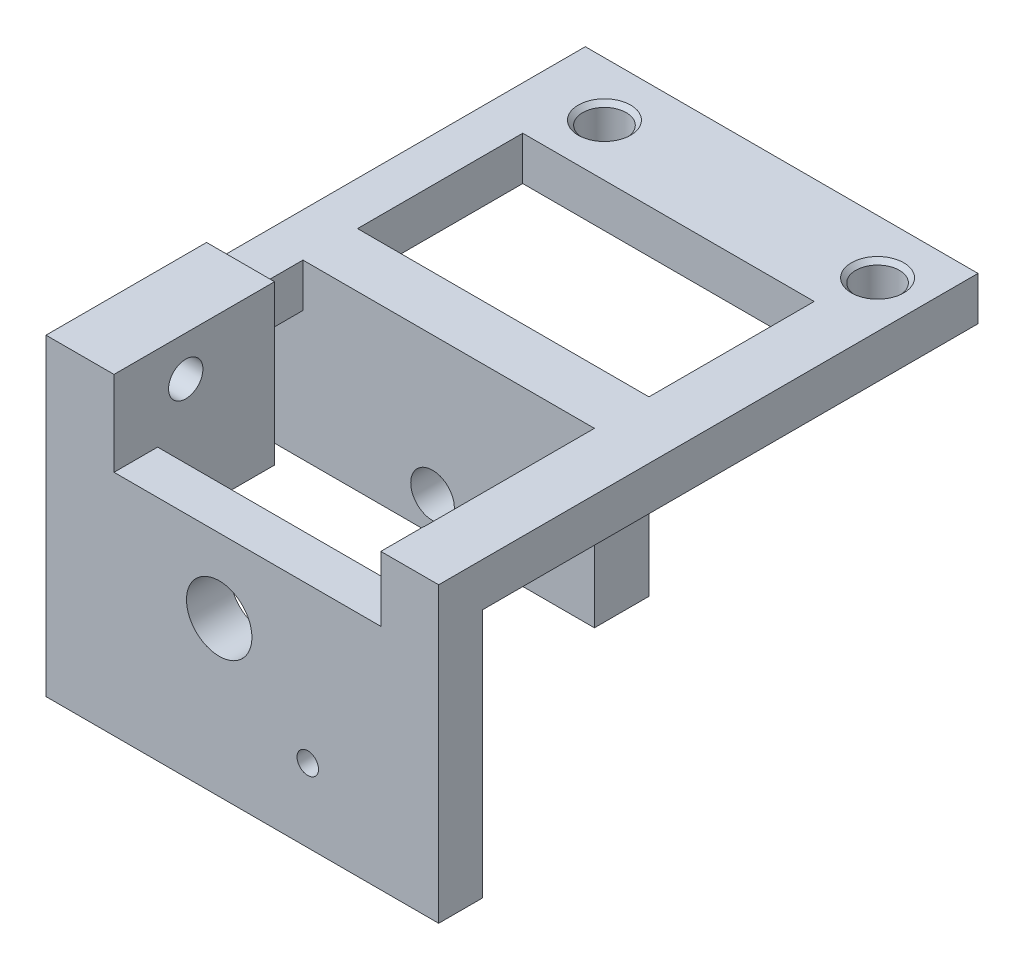
SolidWorks part; units mm, degrees
material "ABS"
ref_plane "Front Plane" through (0, 0, 0) normal (0, 0, 1) x (1, 0, 0)
ref_plane "Top Plane" through (0, 0, 0) normal (0, 1, 0) x (1, 0, 0)
ref_plane "Right Plane" through (0, 0, 0) normal (1, 0, 0) x (0, 0, -1)
sketch "Sketch1" plane through (0, 0, 0) normal (0, 0, 1) x (1, 0, 0)
  line L0 (0, 8.8442) -> (12.8921, -2.9343) construction
  line L1 (23.5226, 29.0697) -> (31.9421, 29.0697)
  line L2 (-25.2079, 8.8442) -> (-25.2079, -13.6023)
  line L3 (-25.2079, -13.6023) -> (31.9421, -13.6023)
  line L4 (31.9421, 29.0697) -> (31.9421, -13.6023)
  line L6 (-25.2079, 8.8442) -> (-25.2079, 31.9582)
  line L7 (-25.2079, 31.9582) -> (-18.8579, 31.9582)
  line L11 (23.5226, 22.6565) -> (23.5226, 29.0697)
  line L12 (-18.8579, 31.9582) -> (-15.3109, 31.9582)
  line L14 (-15.3109, 31.9582) -> (-15.3109, 22.6565)
  line L15 (-15.3109, 22.6565) -> (-15.3109, 19.6203)
  line L16 (-15.3109, 19.6203) -> (23.5226, 19.6203)
  line L17 (23.5226, 19.6203) -> (23.5226, 22.6565)
  circle A0 centre (12.8921, -2.9343) radius 1.5615
  circle A1 centre (0, 8.8442) radius 4.7625
  point P6 (0, 0)
  dimension "D5" = 9.525
  dimension "D1" = 23.114
  dimension "D2" = 57.15
  dimension "D3" = 42.672
  dimension "D4" = 6.35
  dimension "D6" = 19.05
  dimension "D7" = 10.668
  dimension "D8" = 17.4625
extrude "Boss-Extrude1" add sketch "Sketch1" against normal blind 6.35
sketch "Sketch2" plane through (0, 0, 0) normal (0, 0, 1) x (1, 0, 0)
  line L0 (-25.2079, 31.9582) -> (-25.2079, -13.6023) construction
  line L1 (-18.8579, 31.9582) -> (-25.2079, 31.9582)
  line L3 (-18.8579, 8.8442) -> (-25.2079, 8.8442)
  line L4 (-25.2079, 31.9582) -> (-25.2079, 8.8442)
  line L6 (-15.3109, 31.9582) -> (-25.2079, 31.9582)
  line L7 (-15.3109, 31.9582) -> (-15.3109, 8.8442)
  line L8 (-15.3109, 8.8442) -> (-25.2079, 8.8442)
  line L9 (-25.2079, 31.9582) -> (-25.2079, 8.8442)
  line M4 (-15.3109, 31.9582) -> (-25.2079, 31.9582)
  line M5 (-25.2079, 31.9582) -> (-25.2079, -13.6023)
  line M15 (-15.3109, 19.6203) -> (-15.3109, 31.9582)
  dimension "D1" = 23.114
extrude "Boss-Extrude2" add sketch "Sketch2" against normal blind 23.368 contours L8 L7 L3 M15 M4 M5
sketch "Sketch3" plane through (0, 29.0697, 0) normal (0, 1, 0) x (1, 0, 0)
  line L0 (-25.2079, 23.368) -> (-25.2079, 0) construction
  line L1 (-18.8579, 0) -> (-25.2079, 0)
  line L2 (-18.8579, 0) -> (-18.8579, 76.2)
  line L3 (-18.8579, 76.2) -> (-25.2079, 76.2)
  line L4 (-25.2079, 0) -> (-25.2079, 76.2)
  line L5 (31.9421, 0) -> (23.5601, 0)
  line L6 (31.9421, 0) -> (31.9421, 76.2)
  line L7 (31.9421, 76.2) -> (23.5601, 76.2)
  line L8 (23.5601, 0) -> (23.5601, 76.2)
  dimension "D2" = 8.382
  dimension "D3" = 76.2
  dimension "D4" = 76.2
extrude "Boss-Extrude3" add sketch "Sketch3" against normal blind 6.35
sketch "Sketch4" plane through (-25.2079, 0, 0) normal (-1, 0, 0) x (0, 0, 1)
  circle A0 centre (-10.4375, 26.1623) radius 2.5
  dimension "D1" = 5
extrude "Cut-Extrude1" cut sketch "Sketch4" against normal up to next
sketch "Sketch5" plane through (0, 29.0697, 0) normal (0, 1, 0) x (1, 0, 0)
  line L0 (31.9421, 76.2) -> (31.9421, 0) construction
  line L1 (-25.2079, 78.4946) -> (31.9421, 78.4946)
  line L2 (-25.2079, 78.4946) -> (-25.2079, 63.0363)
  line L3 (-25.2079, 63.0363) -> (31.9421, 63.0363)
  line L4 (31.9421, 78.4946) -> (31.9421, 63.0363)
  line L5 (-25.2079, 76.2) -> (-25.2079, 23.368) construction
extrude "Boss-Extrude4" add sketch "Sketch5" against normal blind 6.35
hole_wizard "1/4 (0.25) Diameter Hole1" positions "Sketch6" profile "Sketch7" hole size "1/4" standard "ANSI Inch" end condition through all
sketch "Sketch6" plane through (0, 29.0697, 0) normal (0, 1, 0) x (1, 0, 0)
  point P0 (-14.5536, 70.6253)
  point P2 (25.1952, 70.6253)
sketch "Sketch7" plane through (-14.5536, 29.0697, -70.6253) normal (1, 0, 0) x (0, 0, 1)
  line L0 (0, 0) -> (0, 42.672)
  line L1 (0, 42.672) -> (3.175, 42.672)
  line L2 (3.175, 42.672) -> (3.175, 0.635)
  line L3 (3.175, 0.635) -> (3.81, 0)
  line L5 (3.81, 0) -> (0, 0)
  line L6 (-3.175, 0.635) -> (-3.81, 0) construction
  line L11 (0, -6.35) -> (0, 107.95) construction
  dimension "Thru Hole Dia." = 6.35
  dimension "Thru Hole Depth" = 42.672
  dimension "Near C'Sink Dia." = 7.62
  dimension "Near C'Sink Angle" = 90
sketch "Sketch8" plane through (0, 29.0697, 0) normal (0, 1, 0) x (1, 0, 0)
  line L0 (-25.2079, 78.4946) -> (-25.2079, 23.368) construction
  line L10 (-25.2079, 38.9875) -> (23.5601, 38.9875)
  line L11 (23.5601, 63.0363) -> (23.5601, 6.35) construction
  line L12 (23.5601, 38.9875) -> (23.5601, 31.05)
  line L13 (23.5601, 31.05) -> (-25.2079, 31.05)
  line L14 (-25.2079, 38.9875) -> (-25.2079, 31.05)
extrude "Boss-Extrude5" add sketch "Sketch8" against normal blind 25.146
sketch "Sketch10" plane through (0, 0, -38.9875) normal (0, 0, -1) x (-1, 0, 0)
  circle A0 centre (0, 8.8442) radius 3.175
  dimension "D1" = 6.35
extrude "Cut-Extrude2" cut sketch "Sketch10" against normal up to next
